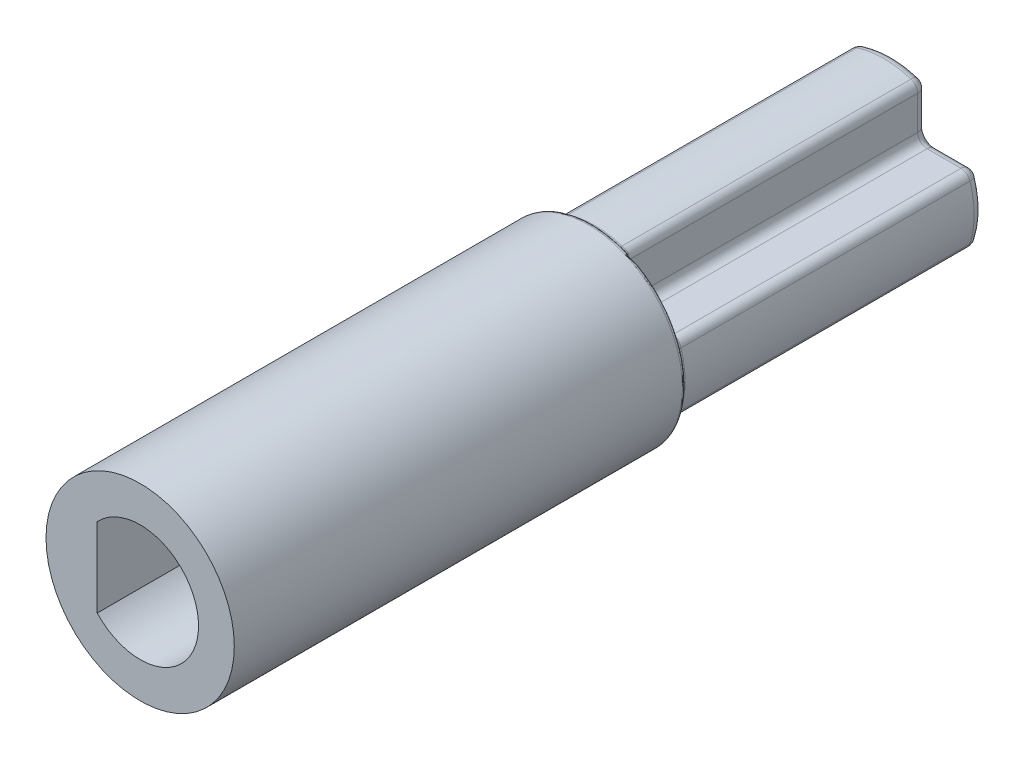
SolidWorks part; units mm, degrees
ref_plane "Front Plane" through (0, 0, 0) normal (0, 0, 1) x (1, 0, 0)
ref_plane "Top Plane" through (0, 0, 0) normal (0, 1, 0) x (1, 0, 0)
ref_plane "Right Plane" through (0, 0, 0) normal (1, 0, 0) x (0, 0, -1)
sketch "Sketch2" plane through (0, 0, 0) normal (0, 0, 1) x (1, 0, 0)
  line L0 (-1.1402, 1.05) -> (-1.1402, -1.05)
  arc A0 (-1.1402, -1.05) -> (-1.1402, 1.05) centre (0, 0) ccw
  circle A1 centre (0, 0) radius 2.5
  dimension "D1" = 3.1
  dimension "D2" = 5
  dimension "D3" = 2.1
extrude "Boss-Extrude1" add sketch "Sketch2" along normal blind 10 contours A1 | A0 L0
sketch "Sketch3" plane through (0, 0, 0) normal (0, 0, -1) x (-1, 0, 0)
  circle A0 centre (0, 0) radius 2.5
extrude "Boss-Extrude2" add sketch "Sketch3" along normal blind 2
sketch "Sketch4" plane through (0, 0, -2) normal (0, 0, -1) x (-1, 0, 0)
  line L2 (-2.0457, 0.895) -> (-1.145, 0.895)
  line L3 (-0.895, 1.145) -> (-0.895, 2.0457)
  line L8 (0.895, 2.0457) -> (0.895, 1.145)
  line L9 (1.145, 0.895) -> (2.0457, 0.895)
  line L14 (2.0457, -0.895) -> (1.145, -0.895)
  line L15 (0.895, -1.145) -> (0.895, -2.0457)
  line L20 (-0.895, -2.0457) -> (-0.895, -1.145)
  line L21 (-1.145, -0.895) -> (-2.0457, -0.895)
  arc A0 (-2.2842, 0.7202) -> (-2.2842, -0.7202) centre (0, 0) ccw
  arc A1 (0.7202, 2.2842) -> (-0.7202, 2.2842) centre (0, 0) ccw
  arc A2 (2.2842, -0.7202) -> (2.2842, 0.7202) centre (0, 0) ccw
  arc A3 (-0.7202, -2.2842) -> (0.7202, -2.2842) centre (0, 0) ccw
  arc A5 (-0.895, -2.0457) -> (-0.7202, -2.2842) centre (-0.645, -2.0457) ccw
  arc A6 (0.7202, -2.2842) -> (0.895, -2.0457) centre (0.645, -2.0457) ccw
  arc A7 (2.0457, -0.895) -> (2.2842, -0.7202) centre (2.0457, -0.645) ccw
  arc A8 (2.2842, 0.7202) -> (2.0457, 0.895) centre (2.0457, 0.645) ccw
  arc A9 (0.895, 2.0457) -> (0.7202, 2.2842) centre (0.645, 2.0457) ccw
  arc A10 (-0.7202, 2.2842) -> (-0.895, 2.0457) centre (-0.645, 2.0457) ccw
  arc A11 (-2.2842, 0.7202) -> (-2.0457, 0.895) centre (-2.0457, 0.645) cw
  arc A12 (-2.2842, -0.7202) -> (-2.0457, -0.895) centre (-2.0457, -0.645) ccw
  arc A13 (-1.145, -0.895) -> (-0.895, -1.145) centre (-1.145, -1.145) cw
  arc A14 (0.895, -1.145) -> (1.145, -0.895) centre (1.145, -1.145) cw
  arc A15 (1.145, 0.895) -> (0.895, 1.145) centre (1.145, 1.145) cw
  arc A16 (-0.895, 1.145) -> (-1.145, 0.895) centre (-1.145, 1.145) cw
  point P3 (-2.395, 0)
  point P11 (2.395, 0)
  point P13 (0, 2.395)
  point P16 (-0.895, -2.2215)
  point P23 (2.2215, -0.895)
  point P28 (0.895, 2.2215)
  dimension "D2" = 1.5
  dimension "D7" = 0.25
  dimension "D6" = 1.5
  dimension "D8" = 0.25
  dimension "D1" = 4
  dimension "D3" = 1.79
  dimension "D4" = 1.5
  dimension "D5" = 1.5
extrude "Boss-Extrude3" add sketch "Sketch4" along normal blind 8 contours A16 L2 A11 A0 A12 L21 A13 L20 A5 A3 A6 L15 A14 L14 A7 A2 A8 L9 A15 L8 A9 A1 A10 L3
fillet "Fillet1" radius 0.25 24 edges at (2.1936, 0.8466, -10) (2.395, 0, -10) (2.1936, -0.8466, -10) (1.5954, -0.895, -10) (0.9682, -0.9682, -10) (0.895, -1.5954, -10) (0.8466, -2.1936, -10) (0, -2.395, -10) (-0.8466, -2.1936, -10) (-0.895, -1.5954, -10) (-0.9682, -0.9682, -10) (-1.5954, -0.895, -10) (-2.1936, -0.8466, -10) (-2.395, 0, -10) (-2.1936, 0.8466, -10) (-1.5954, 0.895, -10) (-0.9682, 0.9682, -10) (-0.895, 1.5954, -10) (-0.8466, 2.1936, -10) (0, 2.395, -10) (0.8466, 2.1936, -10) (0.895, 1.5954, -10) (0.9682, 0.9682, -10) (1.5954, 0.895, -10)
fillet "Fillet2" radius 0.1 1 edges at (-2.5, 0, -2)
fillet "Fillet3" radius 0.1 24 edges at (-0.895, -1.5954, -2) (-0.8466, -2.1936, -2) (0, -2.395, -2) (0.8466, -2.1936, -2) (0.895, -1.5954, -2) (0.9682, -0.9682, -2) (1.5954, -0.895, -2) (2.1936, -0.8466, -2) (2.395, 0, -2) (2.1936, 0.8466, -2) (1.5954, 0.895, -2) (0.9682, 0.9682, -2) (0.895, 1.5954, -2) (0.8466, 2.1936, -2) (0, 2.395, -2) (-0.8466, 2.1936, -2) (-0.895, 1.5954, -2) (-0.9682, 0.9682, -2) (-1.5954, 0.895, -2) (-2.1936, 0.8466, -2) (-2.395, 0, -2) (-2.1936, -0.8466, -2) (-1.5954, -0.895, -2) (-0.9682, -0.9682, -2)
sketch "Sketch5" plane through (0, 0, -10) normal (0, 0, -1) x (-1, 0, 0)
  circle A0 centre (0, 0) radius 1
  dimension "D1" = 2
extrude "Cut-Extrude1" cut sketch "Sketch5" against normal through all
